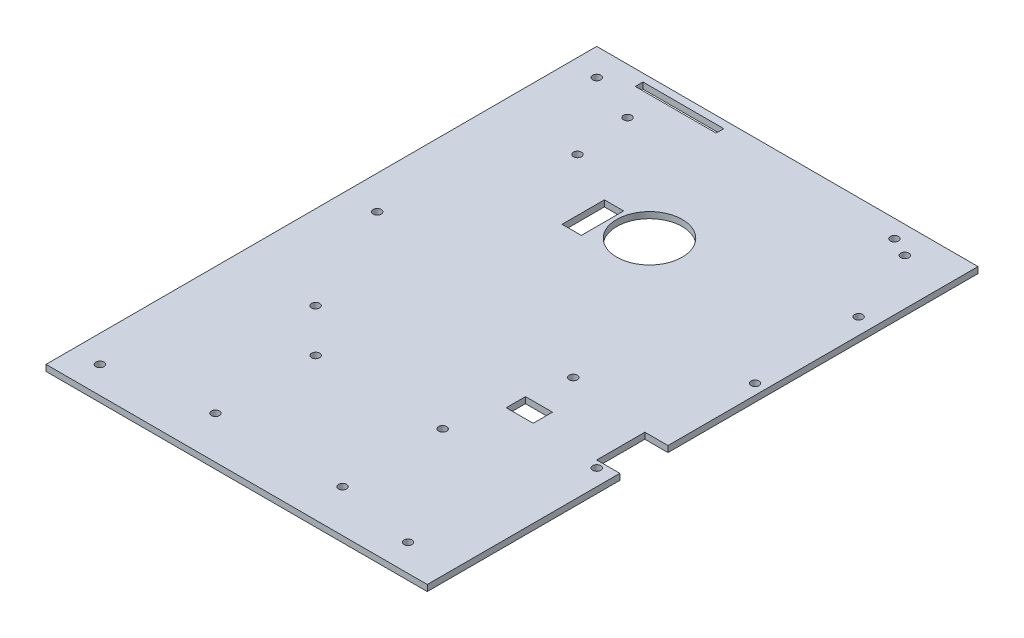
SolidWorks part; units mm, degrees
ref_plane "前视基准面" through (0, 0, 0) normal (0, 0, 1) x (1, 0, 0)
ref_plane "上视基准面" through (0, 0, 0) normal (0, 1, 0) x (1, 0, 0)
ref_plane "右视基准面" through (0, 0, 0) normal (1, 0, 0) x (0, 0, -1)
sketch "草图1" plane through (0, 0, 0) normal (0, 1, 0) x (1, 0, 0)
  line L1 (0, 0) -> (99, 0)
  line L2 (0, 0) -> (0, -99)
  line L3 (0, -99) -> (99, -99)
  line L4 (99, 0) -> (99, -99)
  line L5 (21.8, -26.8) -> (94.8, -26.8) construction
  line L6 (21.8, -26.8) -> (21.8, -94.8) construction
  line L7 (21.8, -94.8) -> (94.8, -94.8) construction
  line L8 (94.8, -26.8) -> (94.8, -94.8) construction
  line L9 (0, -99) -> (99, -99)
  line L10 (0, -99) -> (0, -143)
  line L11 (0, -143) -> (99, -143)
  line L12 (99, -99) -> (99, -143)
  line L13 (5, -5) -> (89, -5) construction
  line L14 (5, -5) -> (5, -138) construction
  line L15 (5, -138) -> (89, -138) construction
  line L16 (89, -5) -> (89, -138) construction
  line L17 (7, -7) -> (87, -7) construction
  line L18 (7, -7) -> (7, -136) construction
  line L19 (7, -136) -> (87, -136) construction
  line L20 (87, -7) -> (87, -136) construction
  line L21 (31, -104) -> (68, -104) construction
  line L22 (31, -104) -> (31, -134) construction
  line L23 (31, -134) -> (68, -134) construction
  line L24 (68, -104) -> (68, -134) construction
  line L25 (33, -106) -> (66, -106) construction
  line L26 (33, -106) -> (33, -132) construction
  line L27 (33, -132) -> (66, -132) construction
  line L28 (66, -106) -> (66, -132) construction
  line L29 (14, -2) -> (35, -2)
  line L30 (14, -2) -> (14, -4)
  line L31 (14, -4) -> (35, -4)
  line L32 (35, -2) -> (35, -4)
  line L33 (99, -80.5) -> (93, -80.5)
  line L34 (99, -80.5) -> (99, -93)
  line L35 (99, -93) -> (93, -93)
  line L36 (93, -80.5) -> (93, -93)
  line L37 (40.5, -33.5) -> (35.5, -33.5)
  line L38 (40.5, -33.5) -> (40.5, -44.5)
  line L39 (40.5, -44.5) -> (35.5, -44.5)
  line L40 (35.5, -33.5) -> (35.5, -44.5)
  line L41 (69.5, -88) -> (76.5, -88)
  line L42 (69.5, -88) -> (69.5, -93)
  line L43 (69.5, -93) -> (76.5, -93)
  line L44 (76.5, -88) -> (76.5, -93)
  circle A0 centre (21.8, -26.8) radius 1.05
  circle A1 centre (94.8, -26.8) radius 1.05
  circle A2 centre (21.8, -94.8) radius 1.05
  circle A3 centre (94.8, -94.8) radius 1.05
  circle A4 centre (8.7, -65.7) radius 1.05
  circle A5 centre (81.9, -4.6) radius 1.05
  circle A6 centre (96.3, -55.2) radius 1.05
  circle A7 centre (20, -12) radius 1.05
  circle A8 centre (71.4, -77.5) radius 1.05
  circle A9 centre (7, -7) radius 1.05
  circle A10 centre (87, -7) radius 1.05
  circle A11 centre (7, -136) radius 1.05
  circle A12 centre (87, -136) radius 1.05
  circle A13 centre (50, -36.3) radius 8.5
  circle A14 centre (33, -106) radius 1.05
  circle A15 centre (66, -106) radius 1.05
  circle A16 centre (33, -132) radius 1.05
  circle A17 centre (66, -132) radius 1.05
  dimension "D7" = 2.1
  dimension "D8" = 2.1
  dimension "D9" = 2.1
  dimension "D10" = 2.1
  dimension "D21" = 2.1
  dimension "D22" = 2.1
  dimension "D23" = 2.1
  dimension "D24" = 2.1
  dimension "D25" = 2.1
  dimension "D33" = 2.1
  dimension "D34" = 2.1
  dimension "D35" = 2.1
  dimension "D36" = 2.1
  dimension "D39" = 17
  dimension "D48" = 2.1
  dimension "D49" = 2.1
  dimension "D50" = 2.1
  dimension "D51" = 2.1
  dimension "D1" = 99
  dimension "D2" = 99
  dimension "D3" = 21.8
  dimension "D4" = 4.2
  dimension "D5" = 68
  dimension "D6" = 73
  dimension "D11" = 8.7
  dimension "D12" = 33.3
  dimension "D13" = 81.9
  dimension "D14" = 94.4
  dimension "D15" = 96.3
  dimension "D16" = 43.8
  dimension "D17" = 20
  dimension "D18" = 87
  dimension "D19" = 71.4
  dimension "D20" = 21.5
  dimension "D26" = 143
  dimension "D27" = 2
  dimension "D28" = 2
  dimension "D29" = 2
  dimension "D30" = 2
  dimension "D31" = 84
  dimension "D32" = 133
  dimension "D37" = 5
  dimension "D38" = 5
  dimension "D40" = 50
  dimension "D41" = 36.3
  dimension "D42" = 2
  dimension "D43" = 2
  dimension "D44" = 2
  dimension "D45" = 2
  dimension "D46" = 37
  dimension "D47" = 30
  dimension "D52" = 5
  dimension "D53" = 31
  dimension "D54" = 14
  dimension "D55" = 21
  dimension "D56" = 2
  dimension "D57" = 2
  dimension "D58" = 6
  dimension "D59" = 50
  dimension "D60" = 12.5
  dimension "D61" = 35.5
  dimension "D62" = 5
  dimension "D63" = 33.5
  dimension "D64" = 11
  dimension "D65" = 6
  dimension "D66" = 5
  dimension "D67" = 22.5
  dimension "D68" = 7
extrude "凸台-拉伸1" add sketch "草图1" along normal blind 1.6 contours L4 L1 L2 L3 A10 A9 A8 A7 A6 A5 A4 A3 A2 A1 A0 | L12 L3 L10 L11 A12 A11
